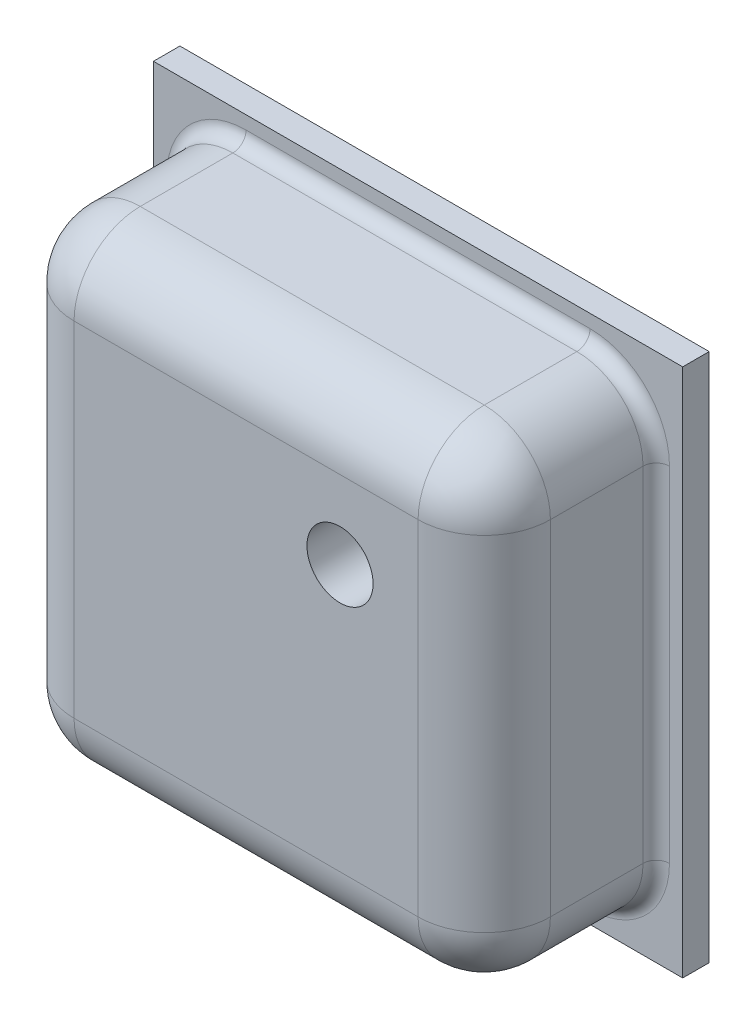
SolidWorks part; units mm, degrees
ref_plane "Plan de face" through (0, 0, 0) normal (0, 0, 1) x (1, 0, 0)
ref_plane "Plan de dessus" through (0, 0, 0) normal (0, 1, 0) x (1, 0, 0)
ref_plane "Plan de droite" through (0, 0, 0) normal (1, 0, 0) x (0, 0, -1)
sketch "Esquisse1" plane through (0, 0, 0) normal (0, 0, 1) x (1, 0, 0)
  line L1 (-1, 1) -> (1, 1)
  line L2 (-1, 1) -> (-1, -1)
  line L3 (-1, -1) -> (1, -1)
  line L4 (1, 1) -> (1, -1)
  line L5 (-1, 1) -> (1, -1) construction
  line L6 (-1, -1) -> (1, 1) construction
  point P0 (0, 0)
  dimension "D1" = 2
extrude "semelle" add sketch "Esquisse1" along normal blind 0.1
sketch "Esquisse2" plane through (0, 0, 0) normal (0, 0, 1) x (1, 0, 0)
  line L8 (0.9, -0.9) -> (0.9, 0.9)
  line L9 (0.9, 0.9) -> (-0.9, 0.9)
  line L10 (-0.9, 0.9) -> (-0.9, -0.9)
  line L11 (-0.9, -0.9) -> (0.9, -0.9)
  line L12 (0.9, -0.9) -> (0.9, 0.9)
  line L13 (0.9, 0.9) -> (-0.9, 0.9)
  line L14 (-0.9, 0.9) -> (-0.9, -0.9)
  line L15 (-0.9, -0.9) -> (0.9, -0.9)
  dimension "D1" = 0.1
extrude "corp" add sketch "Esquisse2" along normal blind 0.75
sketch "Esquisse3" plane through (0, 0, 0.75) normal (0, 0, 1) x (1, 0, 0)
  line L0 (1, -1) -> (1, 1) construction
  line L1 (1, 1) -> (-1, 1) construction
  circle A0 centre (0.355, 0.355) radius 0.125
  point P4 (0, 0)
  dimension "D1" = 0.25
  dimension "D2" = 0.645
  dimension "D3" = 0.645
extrude "event" cut sketch "Esquisse3" against normal up to surface (0.65 mm away) up to face at (0, 0, 0.1)
fillet "conge top" radius 0.25 8 edges at (0, -0.9, 0.75) (0.9, 0, 0.75) (0, 0.9, 0.75) (-0.9, 0, 0.75) (-0.9, 0.9, 0.425) (-0.9, -0.9, 0.425) (0.9, 0.9, 0.425) (0.9, -0.9, 0.425)
fillet "Congé base" radius 0.05 8 edges at (0.8268, -0.8268, 0.1) (0.9, 0, 0.1) (0.8268, 0.8268, 0.1) (0, 0.9, 0.1) (-0.8268, 0.8268, 0.1) (-0.9, 0, 0.1) (-0.8268, -0.8268, 0.1) (0, -0.9, 0.1)
